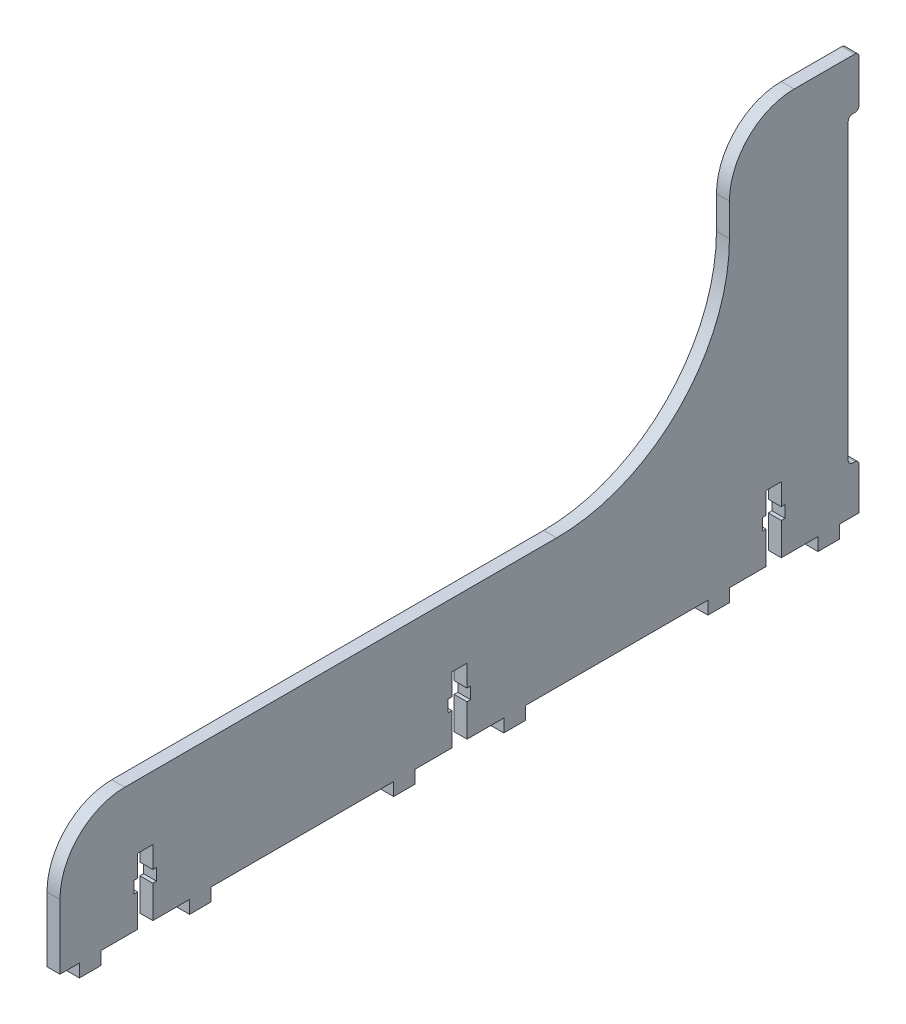
SolidWorks part; units mm, degrees
ref_plane "Front Plane" through (0, 0, 0) normal (0, 0, 1) x (1, 0, 0)
ref_plane "Top Plane" through (0, 0, 0) normal (0, 1, 0) x (1, 0, 0)
ref_plane "Right Plane" through (0, 0, 0) normal (1, 0, 0) x (0, 0, -1)
sketch "Sketch1" plane through (0, 0, 0) normal (1, 0, 0) x (0, 0, -1)
  line L0 (-185, -92.5) -> (185, 92.5) construction
  line L1 (183, 92.5) -> (155, 92.5)
  line L2 (-185, -92.5) -> (-185, -62.5)
  line L3 (-185, -92.5) -> (-176, -92.5)
  line L4 (185, -92.5) -> (185, -73)
  line L5 (0, -32.5) -> (0, -92.5) construction
  line L6 (149, -92.5) -> (149, -77.5)
  line L7 (149, -77.5) -> (150.7, -77.5)
  line L8 (150.7, -77.5) -> (150.7, -72)
  line L9 (150.7, -72) -> (149, -72)
  line L10 (149, -72) -> (149, -62)
  line L11 (149, -62) -> (142, -62)
  line L12 (142, -62) -> (142, -72)
  line L13 (142, -72) -> (140.3, -72)
  line L14 (140.3, -72) -> (140.3, -77.5)
  line L15 (140.3, -77.5) -> (142, -77.5)
  line L16 (142, -77.5) -> (142, -92.5)
  line L17 (166, -92.5) -> (166, -98.5)
  line L18 (166, -98.5) -> (176, -98.5)
  line L19 (176, -98.5) -> (176, -92.5)
  line L20 (115, -92.5) -> (115, -98.5)
  line L21 (115, -98.5) -> (125, -98.5)
  line L22 (125, -98.5) -> (125, -92.5)
  line L23 (30.5, -92.5) -> (30.5, -98.5)
  line L24 (30.5, -98.5) -> (20.5, -98.5)
  line L25 (20.5, -98.5) -> (20.5, -92.5)
  line L26 (-20.5, -92.5) -> (-20.5, -98.5)
  line L27 (-20.5, -98.5) -> (-30.5, -98.5)
  line L28 (-30.5, -98.5) -> (-30.5, -92.5)
  line L29 (-115, -92.5) -> (-115, -98.5)
  line L30 (-115, -98.5) -> (-125, -98.5)
  line L31 (-125, -98.5) -> (-125, -92.5)
  line L32 (-176, -92.5) -> (-176, -98.5)
  line L33 (-176, -98.5) -> (-166, -98.5)
  line L34 (-166, -98.5) -> (-166, -92.5)
  line L35 (166, -95.5) -> (125, -95.5) construction
  line L36 (115, -95.5) -> (30.5, -95.5) construction
  line L37 (20.5, -95.5) -> (-20.5, -95.5) construction
  line L38 (-30.5, -95.5) -> (-115, -95.5) construction
  line L39 (-125, -95.5) -> (-166, -95.5) construction
  line L40 (-166, -92.5) -> (-125, -92.5)
  line L41 (-115, -92.5) -> (-30.5, -92.5)
  line L42 (-20.5, -92.5) -> (20.5, -92.5)
  line L43 (30.5, -92.5) -> (115, -92.5)
  line L44 (125, -92.5) -> (166, -92.5)
  line L45 (145.5, -62) -> (145.5, -92.5) construction
  line L46 (176, -92.5) -> (185, -92.5)
  line L47 (72.75, -92.5) -> (72.75, -27.5329) construction
  line L48 (-3.5, -92.5) -> (-3.5, -77.5)
  line L49 (-3.5, -77.5) -> (-5.2, -77.5)
  line L50 (-5.2, -77.5) -> (-5.2, -72)
  line L51 (-5.2, -72) -> (-3.5, -72)
  line L52 (-3.5, -72) -> (-3.5, -62)
  line L53 (-3.5, -62) -> (3.5, -62)
  line L54 (3.5, -62) -> (3.5, -72)
  line L55 (3.5, -72) -> (5.2, -72)
  line L56 (5.2, -72) -> (5.2, -77.5)
  line L57 (5.2, -77.5) -> (3.5, -77.5)
  line L58 (3.5, -77.5) -> (3.5, -92.5)
  line L59 (-149, -92.5) -> (-149, -77.5)
  line L60 (-149, -77.5) -> (-150.7, -77.5)
  line L61 (-150.7, -77.5) -> (-150.7, -72)
  line L62 (-150.7, -72) -> (-149, -72)
  line L63 (-149, -72) -> (-149, -62)
  line L64 (-149, -62) -> (-142, -62)
  line L65 (-142, -62) -> (-142, -72)
  line L66 (-142, -72) -> (-140.3, -72)
  line L67 (-140.3, -72) -> (-140.3, -77.5)
  line L68 (-142, -77.5) -> (-142, -92.5)
  line L69 (-140.3, -77.5) -> (-142, -77.5)
  line L70 (183, -71) -> (182, -71)
  line L71 (-155, -32.5) -> (45, -32.5)
  line L72 (125, 47.5) -> (125, 62.5)
  line L73 (180, -69) -> (180, 67)
  line L74 (182, 69) -> (183, 69)
  line L75 (185, 71) -> (185, 90.5)
  arc A0 (125, 47.5) -> (45, -32.5) centre (45, 47.5) cw
  arc A1 (155, 92.5) -> (125, 62.5) centre (155, 62.5) ccw
  arc A2 (-155, -32.5) -> (-185, -62.5) centre (-155, -62.5) ccw
  arc A3 (185, 90.5) -> (183, 92.5) centre (183, 90.5) ccw
  arc A4 (185, 71) -> (183, 69) centre (183, 71) cw
  arc A5 (182, 69) -> (180, 67) centre (182, 67) ccw
  arc A6 (180, -69) -> (182, -71) centre (182, -69) ccw
  arc A7 (185, -73) -> (183, -71) centre (183, -73) ccw
  point P90 (-185, -32.5)
  point P104 (180, 69)
  point P107 (180, -71)
  point P110 (185, -71)
  dimension "D17" = 80
  dimension "D18" = 30
  dimension "D19" = 30
  dimension "D21" = 2
  dimension "D2" = 370
  dimension "D3" = 7
  dimension "D4" = 10
  dimension "D5" = 5.5
  dimension "D6" = 15
  dimension "D7" = 1.7
  dimension "D8" = 10
  dimension "D9" = 6
  dimension "D10" = 5
  dimension "D11" = 84.5
  dimension "D12" = 41
  dimension "D13" = 10.4
  dimension "D14" = 185
  dimension "D15" = 60
  dimension "D16" = 230
  dimension "D20" = 140
  dimension "D22" = 23.5
  dimension "D23" = 19.5
extrude "Boss-Extrude1" add sketch "Sketch1" along normal mid plane 6
